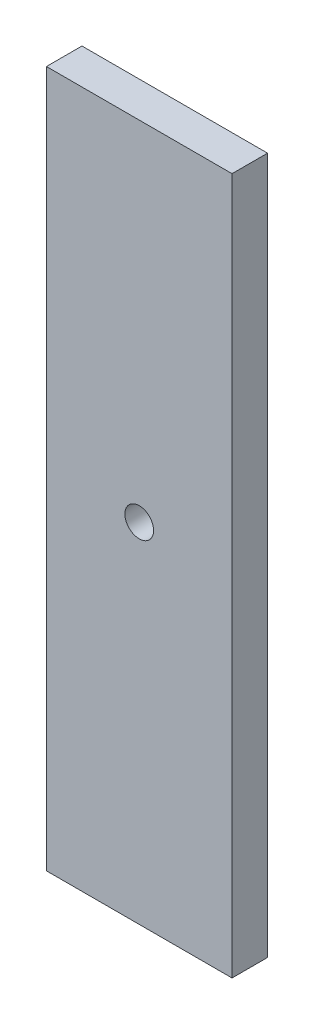
SolidWorks part; units mm, degrees
ref_plane "Front Plane" through (0, 0, 0) normal (0, 0, 1) x (1, 0, 0)
ref_plane "Top Plane" through (0, 0, 0) normal (0, 1, 0) x (1, 0, 0)
ref_plane "Right Plane" through (0, 0, 0) normal (1, 0, 0) x (0, 0, -1)
sketch "Sketch1" plane through (0, 0, 0) normal (0, 0, 1) x (1, 0, 0)
  line L0 (-40, 1.35) -> (-40, 56.15) construction
  line L1 (-47.3, 1.35) -> (-32.7, 1.35)
  line L2 (-47.3, 1.35) -> (-47.3, 56.15)
  line L3 (-47.3, 56.15) -> (-32.7, 56.15)
  line L4 (-32.7, 1.35) -> (-32.7, 56.15)
  line L5 (-47.3, 28.75) -> (-32.7, 28.75) construction
  circle A0 centre (-40, 28.75) radius 1.1294
extrude "Boss-Extrude1" add sketch "Sketch1" along normal blind 2.794
